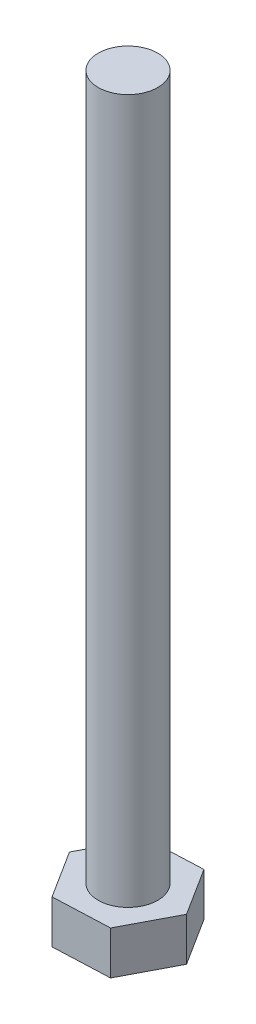
SolidWorks part; units mm, degrees
ref_plane "Front Plane" through (0, 0, 0) normal (0, 0, 1) x (1, 0, 0)
ref_plane "Top Plane" through (0, 0, 0) normal (0, 1, 0) x (1, 0, 0)
ref_plane "Right Plane" through (0, 0, 0) normal (1, 0, 0) x (0, 0, -1)
sketch "Sketch2" plane through (0, 0, 0) normal (0, 1, 0) x (1, 0, 0)
  line L1 (-5.563, 8.778) -> (-10.3835, -0.4287)
  line L2 (-10.3835, -0.4287) -> (-4.8205, -9.2067)
  line L3 (-4.8205, -9.2067) -> (5.563, -8.778)
  line L4 (5.563, -8.778) -> (10.3835, 0.4287)
  line L5 (10.3835, 0.4287) -> (4.8205, 9.2067)
  line L6 (4.8205, 9.2067) -> (-5.563, 8.778)
  circle A0 centre (0, 0) radius 9 construction
  dimension "D1" = 18
extrude "Boss-Extrude1" add sketch "Sketch2" along normal blind 8
sketch "Sketch3" plane through (0, 8, 0) normal (0, 1, 0) x (1, 0, 0)
  circle A0 centre (0, 0) radius 5.5
  dimension "D1" = 11
extrude "Boss-Extrude2" add sketch "Sketch3" along normal blind 130
